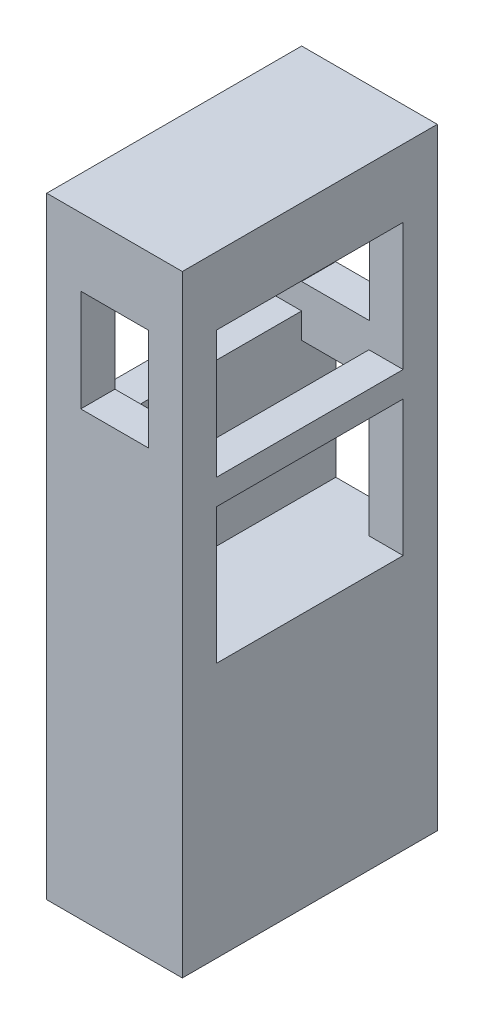
SolidWorks part; units mm, degrees
material "1023 Carbon Steel Sheet (SS)"
ref_plane "Front Plane" through (0, 0, 0) normal (0, 0, 1) x (1, 0, 0)
ref_plane "Top Plane" through (0, 0, 0) normal (0, 1, 0) x (1, 0, 0)
ref_plane "Right Plane" through (0, 0, 0) normal (1, 0, 0) x (0, 0, -1)
sketch "Sketch2" plane through (0, 0, 0) normal (0, 0, 1) x (1, 0, 0)
  line L1 (0, 0) -> (2660, 0)
  line L2 (0, 0) -> (0, 12000)
  line L3 (0, 12000) -> (2660, 12000)
  line L4 (2660, 0) -> (2660, 12000)
  dimension "D1" = 2660
  dimension "D2" = 12000
extrude "Boss-Extrude1" add sketch "Sketch2" along normal blind 5000 contours L2 L1 L4 L3
sketch "Sketch3" plane through (0, 0, 5000) normal (0, 0, 1) x (1, 0, 0)
  line L0 (0, 12000) -> (2660, 12000) construction
  line L1 (667.5, 10670) -> (1997.5, 10670)
  line L2 (667.5, 10670) -> (667.5, 8670)
  line L3 (667.5, 8670) -> (1997.5, 8670)
  line L4 (1997.5, 10670) -> (1997.5, 8670)
  line L6 (0, 0) -> (0, 12000) construction
  dimension "D1" = 1330
  dimension "D2" = 2000
  dimension "D3" = 667.5
  dimension "D4" = 1330
extrude "Cut-Extrude1" cut sketch "Sketch3" against normal blind 5000
sketch "Sketch4" plane through (2660, 0, 0) normal (1, 0, 0) x (0, 0, -1)
  line L0 (-5000, 12000) -> (0, 12000) construction
  line L1 (-4330, 10670) -> (-670, 10670)
  line L2 (-4330, 10670) -> (-4330, 8170)
  line L3 (-4330, 8170) -> (-670, 8170)
  line L4 (-670, 10670) -> (-670, 8170)
  line L5 (-5000, 0) -> (-5000, 12000) construction
  point P4 (-2500, 10670)
  dimension "D1" = 1330
  dimension "D2" = 2500
  dimension "D3" = 3660
  dimension "D4" = 670
extrude "Cut-Extrude2" cut sketch "Sketch4" against normal through all contours L2 L1 L4 L3
sketch "Sketch6" plane through (0, 8170, 0) normal (0, 1, 0) x (1, 0, 0)
  line L0 (0, -4330) -> (2660, -4330) construction
  line L1 (1990, -4330) -> (670, -4330)
  line L2 (1990, -4330) -> (1990, -670)
  line L3 (1990, -670) -> (670, -670)
  line L4 (670, -4330) -> (670, -670)
  line L5 (2660, -4330) -> (2660, -670) construction
  line L6 (0, -4330) -> (0, -670) construction
  line L7 (0, -670) -> (2660, -670) construction
  dimension "D1" = 670
  dimension "D2" = 670
  dimension "D3" = 0
extrude "Cut-Extrude3" cut sketch "Sketch6" against normal blind 2660
sketch "Sketch7" plane through (0, 0, 0) normal (0, 0, -1) x (-1, 0, 0)
  line L1 (-1990, 7670) -> (-667.5, 7670)
  line L2 (-1990, 7670) -> (-1990, 5010)
  line L3 (-1990, 5010) -> (-667.5, 5010)
  line L4 (-667.5, 7670) -> (-667.5, 5010)
  line L5 (-667.5, 8670) -> (-1997.5, 8670) construction
  line L6 (-2660, 0) -> (-2660, 12000) construction
  dimension "D1" = 0
  dimension "D2" = 1000
  dimension "D3" = 2660
  dimension "D4" = 670
extrude "Cut-Extrude6" cut sketch "Sketch7" against normal blind 4269 and the other way through all
sketch "Sketch8" plane through (0, 0, 4269) normal (0, 0, -1) x (-1, 0, 0)
  line L1 (-1990, 5510) -> (-667.5, 5510)
  line L2 (-1990, 5510) -> (-1990, 5010)
  line L3 (-1990, 5010) -> (-667.5, 5010)
  line L4 (-667.5, 5510) -> (-667.5, 5010)
extrude "Cut-Extrude7" cut sketch "Sketch8" against normal up to vertex (61 mm away)
sketch "Sketch11" plane through (667.5, 0, 0) normal (1, 0, 0) x (0, 0, -1)
  line L1 (-4269, 7670) -> (0, 7670)
  line L2 (-4269, 7670) -> (-4269, 5010)
  line L3 (-4269, 5010) -> (0, 5010)
  line L4 (0, 7670) -> (0, 5010)
extrude "Boss-Extrude2" add sketch "Sketch11" along normal up to vertex
sketch "Sketch12" plane through (667.5, 0, 0) normal (1, 0, 0) x (0, 0, -1)
  line L0 (-4269, 5510) -> (-4269, 5010) construction
  line L1 (-4330, 5510) -> (-4269, 5510)
  line L2 (-4330, 5510) -> (-4330, 5010)
  line L3 (-4330, 5010) -> (-4269, 5010)
  line L4 (-4269, 5510) -> (-4269, 5010)
extrude "Boss-Extrude3" add sketch "Sketch12" along normal up to vertex (2.5 mm away) up to point (670, 5510, 4269)
sketch "Sketch13" plane through (2660, 0, 0) normal (1, 0, 0) x (0, 0, -1)
  line L0 (-4330, 10670) -> (-4330, 8170) construction
  line L1 (-670, 5010) -> (-4341.6515, 5010)
  line L2 (-670, 5010) -> (-670, 7670)
  line L3 (-670, 7670) -> (-4341.6515, 7670)
  line L4 (-4341.6515, 5010) -> (-4341.6515, 7670)
  line L5 (-670, 10670) -> (-670, 8170) construction
extrude "Cut-Extrude8" cut sketch "Sketch13" against normal up to vertex (670 mm away) contours L2 L1 L4 L3
sketch "Sketch14" plane through (0, 0, 4341.6515) normal (0, 0, -1) x (-1, 0, 0)
  line L0 (-1990, 5010) -> (-2660, 5010) construction
  line L1 (-2660, 7670) -> (-1990, 7670)
  line L2 (-2660, 7670) -> (-2660, 5010)
  line L3 (-2660, 5010) -> (-1990, 5010)
  line L4 (-1990, 7670) -> (-1990, 5010)
  line L5 (-1990, 5010) -> (-1990, 7670) construction
extrude "Boss-Extrude4" add sketch "Sketch14" along normal up to vertex (11.6515 mm away) up to point (1990, 7670, 4330)
sketch "Sketch15" plane through (0, 0, 0) normal (0, 0, -1) x (-1, 0, 0)
sketch "Sketch16" plane through (0, 10670, 0) normal (0, -1, 0) x (1, 0, 0)
  line L0 (1997.5, 4330) -> (2660, 4330) construction
  line L1 (2460, 4330) -> (200, 4330)
  line L2 (2460, 4330) -> (2460, 670)
  line L3 (2460, 670) -> (200, 670)
  line L4 (200, 4330) -> (200, 670)
  line L5 (0, 670) -> (667.5, 670) construction
  line L6 (0, 4330) -> (0, 670) construction
  line L7 (2660, 4330) -> (2660, 670) construction
  dimension "D1" = 200
  dimension "D2" = 200
extrude "Cut-Extrude9" cut sketch "Sketch16" against normal blind 1000 contours L2 L1 L4 L3
sketch "Sketch17" plane through (0, 0, 0) normal (0, -1, 0) x (1, 0, 0)
  line L0 (2660, 5000) -> (2660, 0) construction
  line L1 (2160, 4500) -> (500, 4500)
  line L2 (2160, 4500) -> (2160, 500)
  line L3 (2160, 500) -> (500, 500)
  line L4 (500, 4500) -> (500, 500)
  line L5 (0, 5000) -> (0, 0) construction
  line L6 (0, 0) -> (2660, 0) construction
  line L7 (0, 5000) -> (2660, 5000) construction
  dimension "D1" = 500
  dimension "D2" = 500
  dimension "D3" = 500
  dimension "D4" = 500
extrude "Cut-Extrude10" cut sketch "Sketch17" against normal blind 4500
